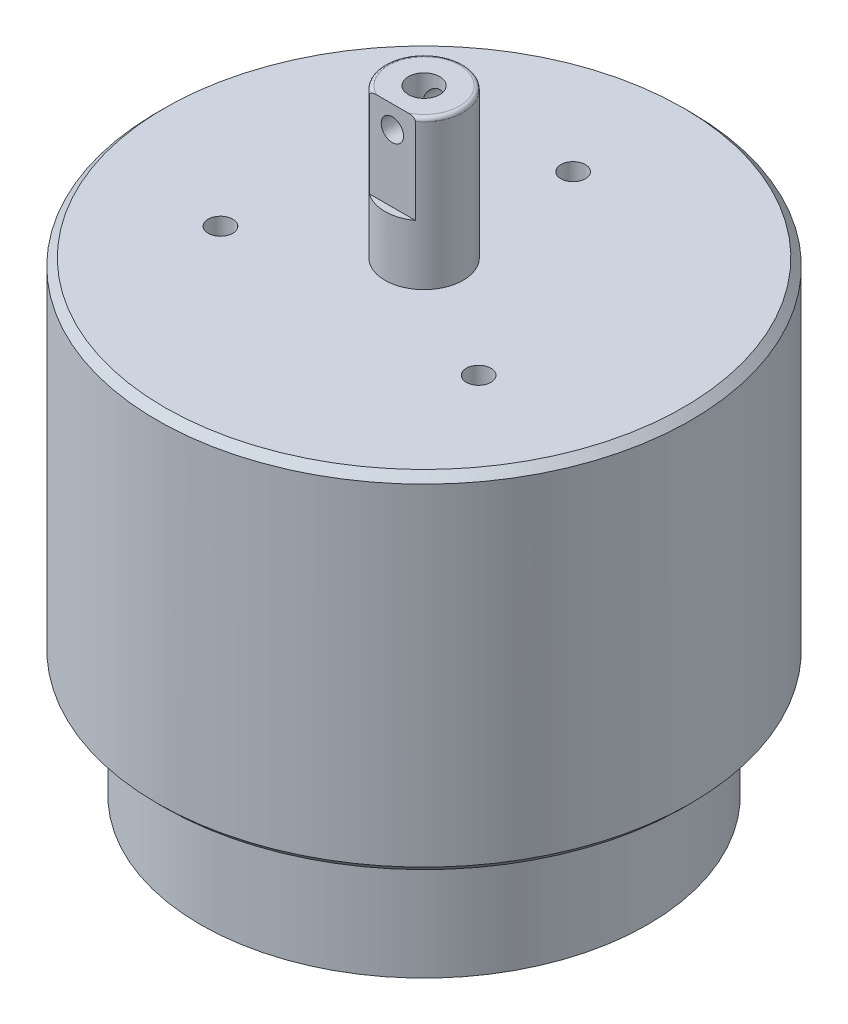
SolidWorks part; units mm, degrees
ref_plane "前视" through (0, 0, 0) normal (0, 0, 1) x (1, 0, 0)
ref_plane "上视" through (0, 0, 0) normal (0, 1, 0) x (1, 0, 0)
ref_plane "右视" through (0, 0, 0) normal (1, 0, 0) x (0, 0, -1)
sketch "草图1" plane through (0, 0, 0) normal (0, 1, 0) x (1, 0, 0)
  circle A0 centre (0, 0) radius 35.8
  dimension "D1" = 71.6
extrude "凸台-拉伸1" add sketch "草图1" along normal mid plane 46.5
sketch "草图2" plane through (0, 23.25, 0) normal (0, 1, 0) x (1, 0, 0)
  line L0 (-50.7598, 0) -> (65.2859, 0) construction
  line L1 (0, 61.6135) -> (0, -53.2896) construction
  point P5 (0, 20)
  point P6 (17.3205, -10)
  point P9 (-17.3205, -10)
  point P10 (0, 0)
  dimension "D1" = 20
  dimension "D2" = 3
hole_wizard "M4 螺纹孔1" positions "3D草图1" profile "草图3" tap size "M4" standard "Gb"
sketch3d "3D草图1"
  point P0 (0, 23.25, -20)
  point P3 (-17.3205, 23.25, 10)
  point P6 (17.3205, 23.25, 10)
sketch "草图3" plane through (0, 23.25, -20) normal (1, 0, 0) x (0, 0, 1)
  line L0 (0, 0) -> (0, 12.4914)
  line L1 (0, 12.4914) -> (1.65, 11.5)
  line L2 (1.65, 11.5) -> (1.65, 0)
  line L5 (1.65, 0) -> (0, 0)
  line L10 (0, 12.4914) -> (-1.65, 11.5) construction
  line L11 (0, -6.35) -> (0, 107.95) construction
  dimension "螺纹孔钻头直径" = 3.3
  dimension "螺纹孔钻头深度" = 11.5
  dimension "导头角度" = 118
cosmetic thread "孔螺蚊线1" parameters "D1"=8, "D2"=4
cosmetic thread "孔螺蚊线2" parameters "D1"=8, "D2"=4
cosmetic thread "孔螺蚊线3" parameters "D1"=8, "D2"=4
sketch "草图4" plane through (0, 23.25, 0) normal (0, 1, 0) x (1, 0, 0)
  circle A0 centre (0, 0) radius 5.25
  dimension "D1" = 10.5
extrude "凸台-拉伸2" add sketch "草图4" along normal blind 20
fillet "圆角1" radius 0.5 1 edges at (0, 43.25, 5.25)
sketch "草图5" plane through (0, 43.25, 0) normal (0, 1, 0) x (1, 0, 0)
  line L0 (0, 61.6135) -> (0, -53.2896) construction
  line L1 (-4.814, -4.25) -> (4.814, -4.25)
  line L2 (-4.814, -4.25) -> (-4.814, -6.25)
  line L3 (-4.814, -6.25) -> (4.814, -6.25)
  line L4 (4.814, -4.25) -> (4.814, -6.25)
  line L5 (-4.814, -4.25) -> (4.814, -6.25) construction
  line L6 (-4.814, -6.25) -> (4.814, -4.25) construction
  circle A0 centre (0, 0) radius 5.25 construction
  point P0 (0, -5.25)
  dimension "D1" = 1
extrude "切除-拉伸1" cut sketch "草图5" against normal blind 12
hole_wizard "M5 螺纹孔1" positions "3D草图2" profile "草图6" tap size "M5" standard "Gb"
sketch3d "3D草图2"
  line L0 (0, 39.9163, 0) -> (0, 48.4175, 0) construction
  point P0 (0, 43.25, 0)
sketch "草图6" plane through (0, 43.25, 0) normal (1, 0, 0) x (0, 0, 1)
  line L0 (0, 0) -> (0, 15.2618)
  line L1 (0, 15.2618) -> (2.1, 14)
  line L2 (2.1, 14) -> (2.1, 0)
  line L5 (2.1, 0) -> (0, 0)
  line L10 (0, 15.2618) -> (-2.1, 14) construction
  line L11 (0, -6.35) -> (0, 107.95) construction
  dimension "螺纹孔钻头直径" = 4.2
  dimension "螺纹孔钻头深度" = 14
  dimension "导头角度" = 118
cosmetic thread "孔螺蚊线4" parameters "D1"=10, "D2"=5
chamfer "倒角1" distance 1 angle 45 1 edges at (0, 23.25, 35.8)
sketch "草图7" plane through (0, -23.25, 0) normal (0, -1, 0) x (1, 0, 0)
  circle A0 centre (0, 0) radius 30
  dimension "D1" = 60
extrude "凸台-拉伸3" add sketch "草图7" along normal blind 17
chamfer "倒角2" distance 1 angle 45 1 edges at (0, -23.25, 35.8)
chamfer "倒角3" distance 1 distance2 3 1 edges at (0, -40.25, -30)
sketch "草图8" plane through (0, 0, 4.25) normal (0, 0, 1) x (1, 0, 0)
  line L0 (2.1213, 43.25) -> (-2.1213, 43.25) construction
  circle A0 centre (0, 40.25) radius 1.5
  dimension "D1" = 3
  dimension "D2" = 3
extrude "切除-拉伸2" cut sketch "草图8" against normal through all
sketch "草图9" plane through (0, 23.25, 0) normal (0, 1, 0) x (1, 0, 0)
  arc A0 (3.0822, -4.25) -> (-3.0822, -4.25) centre (0, 0) ccw construction
  circle A1 centre (17.3205, -10) radius 1.65 construction
  circle A2 centre (-17.3205, -10) radius 1.65 construction
  circle A3 centre (0, 20) radius 1.65 construction
  arc A4 (3.0822, -4.25) -> (-3.0822, -4.25) centre (0, 0) ccw
  circle A5 centre (17.3205, -10) radius 1.65
  circle A6 centre (-17.3205, -10) radius 1.65
  circle A7 centre (0, 20) radius 1.65
